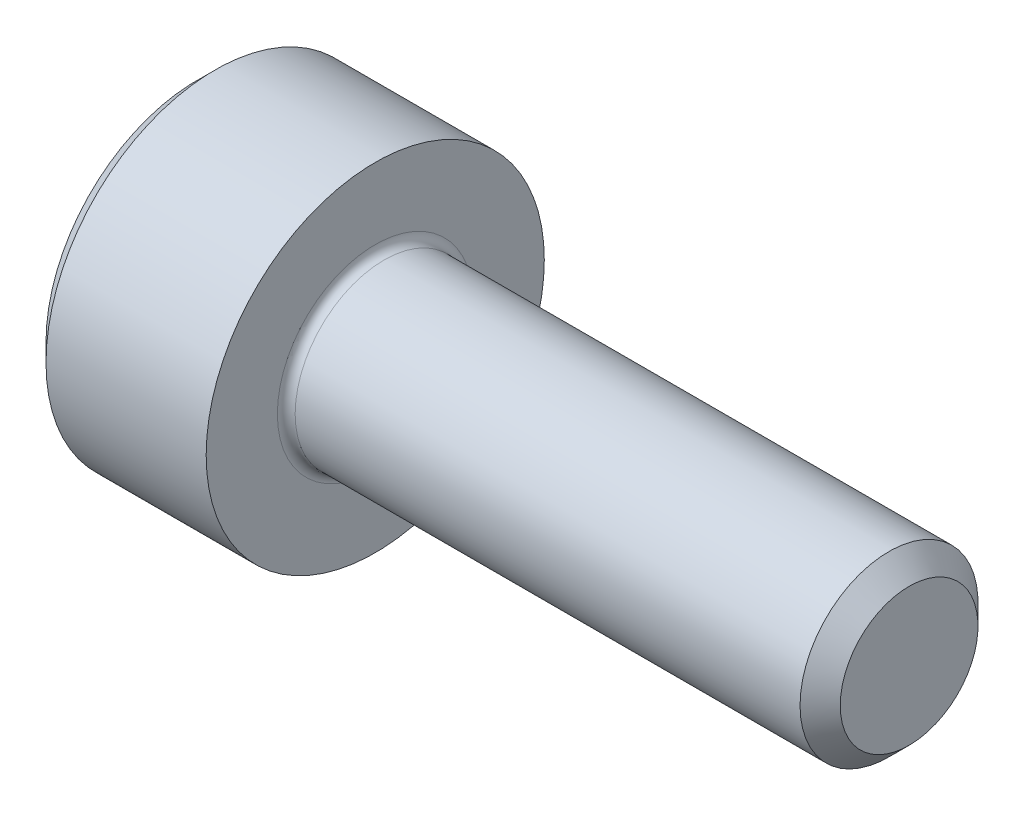
SolidWorks part; units mm, degrees
revolve "Base-Revolve" add sketch "BodySke"
sketch "BodySke" plane through (0, 0, 0) normal (0, 0, 1) x (1, 0, 0)
  line L0 (0, 0) -> (0, 1.7)
  line L1 (0.2, 1.9) -> (2, 1.9)
  line L2 (2, 1.9) -> (2, 1)
  line L3 (2, 1) -> (7.774, 1)
  line L4 (8, 0.774) -> (8, 0)
  line L5 (8, 0) -> (0, 0)
  line L6 (-31.75, 0) -> (127, 0) construction
  line L7 (0, 1.7) -> (0.2, 1.9)
  line L8 (8, 0.774) -> (7.774, 1)
  line L9 (0, -1.7) -> (0.2, -1.9) construction
  line L10 (8, -0.774) -> (7.774, -1) construction
  line L11 (2.4, 9.525) -> (2.4, 3.175) construction
  line L12 (2, 9.525) -> (2, 3.175) construction
  line L13 (-42, 9.525) -> (-42, 3.175) construction
  dimension "Diameter" = 2
  dimension "Head_ht" = 2
  dimension "Length" = 6
  dimension "Body_ch_ang" = 45
  dimension "Head_dia" = 3.8
  dimension "Head_ch_ang" = 45
  dimension "Minor_dia" = 1.548
  dimension "Advance" = 0.4
  dimension "Thread_nom" = 6
  dimension "Thread_length" = 50
  dimension "Head_ch_ht" = 0.2
cosmetic thread "ThreadCosmetic"
fillet "Fillet1" radius 0.1 1 edges at (2, 0, 1)
ref_plane "Plane1" through (0, 0, 0) normal (0, 0, 1) x (1, 0, 0)
ref_plane "Plane2" through (0, 0, 0) normal (0, 1, 0) x (1, 0, 0)
ref_plane "Plane3" through (0, 0, 0) normal (1, 0, 0) x (0, 0, -1)
sketch "Sketch2" plane through (0, 0, 0) normal (0, 0, 1) x (1, 0, 0)
  line L0 (0, 0.7725) -> (1, 0.7725)
  line L1 (1, 0.7725) -> (1.446, 0)
  line L2 (-31.75, 0) -> (127, 0) construction
  line L3 (1.446, 0) -> (0, 0)
  line L4 (0, 0) -> (0, 0.7725)
  line L5 (0, 1.7) -> (0, -1.7) construction
  line L6 (0, 0) -> (47.625, 0) construction
  line L7 (2, -1.9) -> (2, 1.9) construction
  dimension "D1" = 0.7725
  dimension "D2" = 60
revolve "Hex-PreBroach" cut sketch "Sketch2" angle 360 about L6
sketch "Sketch3" plane through (0, 0, 0) normal (-1, 0, 0) x (0, 0.5, 0.866)
  line L0 (0.446, 0.7725) -> (-0.446, 0.7725)
  line L1 (-0.446, 0.7725) -> (-0.892, 0)
  line L2 (0.446, 0.7725) -> (0.892, 0)
  line L3 (0.446, -0.7725) -> (0.892, 0)
  line L4 (0.446, -0.7725) -> (-0.446, -0.7725)
  line L5 (-0.446, -0.7725) -> (-0.892, 0)
  dimension "D1" = 0.7725
  dimension "D2" = 0.7725
  dimension "Hex_size" = 1.545
extrude "Hex" cut sketch "Sketch3" against normal blind 1
sketch "Sketch4" plane through (0, 0, 0) normal (-1, 0, 0) x (0, 0, 1)
  line L0 (0, 0) -> (0.9398, 0)
  line L1 (0, 0) -> (6.1484, 3.5498) construction
  line L2 (0, 0) -> (0.4699, 0.8139)
  line L3 (0.7832, 0.2175) -> (0.8962, 0.2828)
  line L4 (0.58, 0.5695) -> (0.693, 0.6348)
  arc A0 (0.7832, 0.2175) -> (0.58, 0.5695) centre (0, 0) ccw
  arc A1 (0.9398, 0) -> (0.8962, 0.2828) centre (0, 0) ccw
  arc A2 (0.4699, 0.8139) -> (0.693, 0.6348) centre (0, 0) cw
  dimension "D1" = 30
  dimension "D2" = 60
  dimension "Spline_p_dim" = 0.4064
  dimension "D3" = 0.2032
extrude "Spline" [suppressed] cut sketch "Sketch4" against normal blind 1
pattern_circular "CirPattern1" [suppressed] count 6 every 60
sketch "Sketch5" plane through (0, 0, 0) normal (0, 0, 1) x (1, 0, 0)
  line L0 (-31.75, 0) -> (127, 0) construction
  line L2 (0, 1.7) -> (0, -1.7) construction
  circle A0 centre (0.1, 0) radius 0.005
  dimension "Drilled_hole_dia" = 0.01
  dimension "Drilled_hole_loc" = 0.1
extrude "Hole" [suppressed] cut sketch "Sketch5" against normal through all and the other way through all
pattern_circular "Drilled-4" [suppressed] count 2 every 60
pattern_circular "Drilled-6" [suppressed] count 3 every 60
sketch "ThdSchSke" plane through (0, 0, 0) normal (0, 0, 1) x (1, 0, 0)
  line L0 (2.4, -0.774) -> (2.2418, -1)
  line L1 (2.4, -0.774) -> (2.5582, -1)
  line L2 (2.5582, -1) -> (2.5582, -1.25)
  line L3 (-3.175, 0) -> (5.1513, 0) construction
  line L5 (2.5582, -1.25) -> (2.2418, -1.25)
  line L6 (2.2418, -1.25) -> (2.2418, -1)
  line L7 (0, 1.7) -> (0, -1.7) construction
  dimension "Thread_minor" = 1.548
  dimension "Diameter" = 2
  dimension "Start" = 2.4
revolve "ThreadSchematic" [suppressed] cut sketch "ThdSchSke" angle 360 about L3
pattern_linear "ThdSchPat" [suppressed]
equation "\"D2@Sketch3\" = \"Hex_size@Sketch3\" / 2"
equation "\"D1@Sketch3\" = \"Hex_size@Sketch3\" / 2"
equation "\"D1@Sketch2\" = \"Hex_size@Sketch3\" / 2"
equation "\"D3@Sketch4\" = \"Spline_p_dim@Sketch4\" / 2"
equation "\"Thread_minor@ThreadCosmetic\"  =  \"Minor_dia@BodySke\""
equation "\"D2@CirPattern1\" = 360 / \"Num_teeth@CirPattern1\""
equation "\"Wall_thickness@Sketch2\" = \"Head_ht@BodySke\" - \"Key_eng@Hex\""
equation "\"Thread_length@ThreadCosmetic\" = ((sgn( (\"Length@BodySke\" - \"Advance@BodySke\" ) - \"Thread_nom@BodySke\" )-1)*( (\"Length@BodySke\" - \"Advance@BodySke\" ) - \"Thread_nom@BodySke\" ))/-2+ \"Thread_nom@BodySke\""
equation "\"Thread_minor@ThdSchSke\" = \"Minor_dia@BodySke\""
equation "\"Diameter@ThdSchSke\" = \"Diameter@BodySke\""
equation "\"Overcut@ThdSchSke\" = \"Diameter@BodySke\" * 1.25"
equation "\"Start@ThdSchSke\" = \"Head_ht@BodySke\" + \"Length@BodySke\" - \"Thread_length@ThreadCosmetic\"  '---Non-countersunk---"
equation "\"Num_threads@ThdSchPat\" = int( \"Thread_length@ThreadCosmetic\" / \"Advance@BodySke\" + 0.999 )  + 1"
equation "\"Advance@ThdSchPat\" = \"Thread_length@ThreadCosmetic\" /  (\"Num_threads@ThdSchPat\" - 1) 'relax it"
equation "\"Num_threads@ThdSchPat\" = \"Num_threads@ThdSchPat\" - sgn( \"Num_threads@ThdSchPat\" - 1) '---chamfered tips only---"
